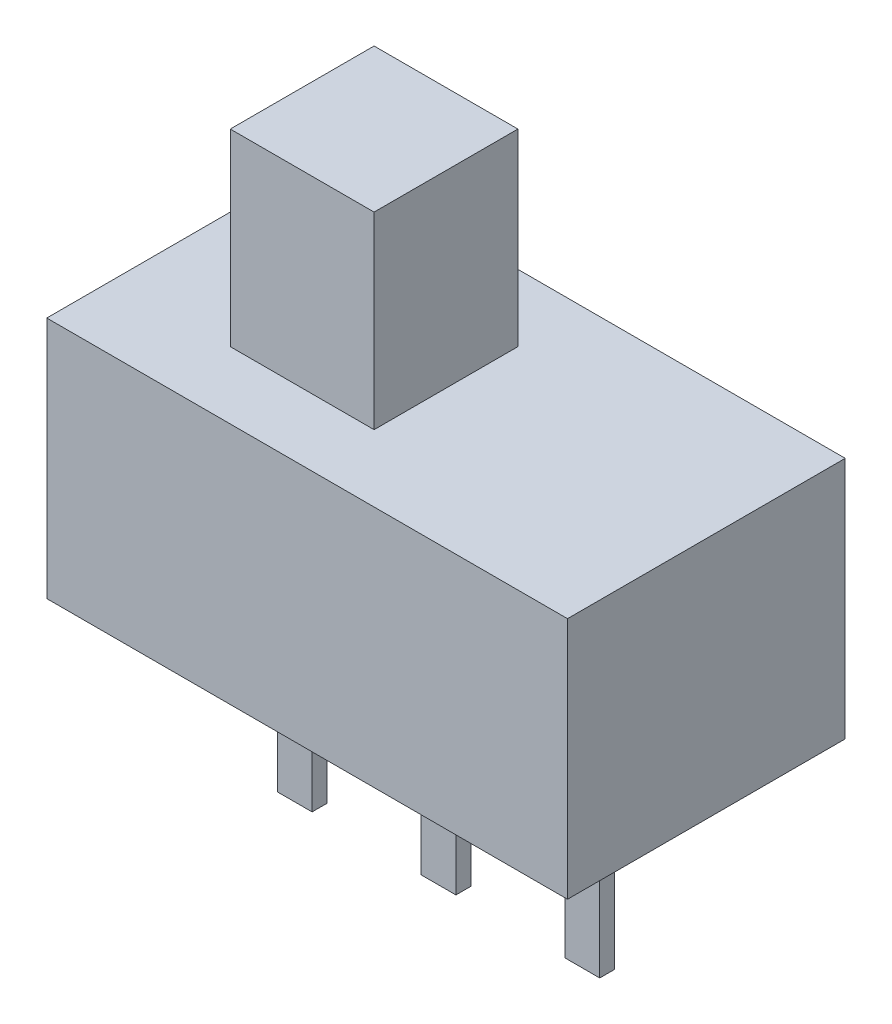
SolidWorks part; units mm, degrees
ref_plane "Plan de face" through (0, 0, 0) normal (0, 0, 1) x (1, 0, 0)
ref_plane "Plan de dessus" through (0, 0, 0) normal (0, 1, 0) x (1, 0, 0)
ref_plane "Plan de droite" through (0, 0, 0) normal (1, 0, 0) x (0, 0, -1)
sketch "Esquisse1" plane through (0, 0, 0) normal (0, 1, 0) x (1, 0, 0)
  line L1 (-5.25, 2.8) -> (5.25, 2.8)
  line L2 (-5.25, 2.8) -> (-5.25, -2.8)
  line L3 (-5.25, -2.8) -> (5.25, -2.8)
  line L4 (5.25, 2.8) -> (5.25, -2.8)
  line L5 (-5.25, 2.8) -> (5.25, -2.8) construction
  line L6 (-5.25, -2.8) -> (5.25, 2.8) construction
  point P0 (0, 0)
  dimension "D1" = 10.5
  dimension "D2" = 5.6
extrude "Boss.-Extru.1" add sketch "Esquisse1" along normal blind 4.9
sketch "Esquisse2" plane through (0, 4.9, 0) normal (0, 1, 0) x (1, 0, 0)
  line L1 (-2.9, 1.45) -> (0, 1.45)
  line L2 (-2.9, 1.45) -> (-2.9, -1.45)
  line L3 (-2.9, -1.45) -> (0, -1.45)
  line L4 (0, 1.45) -> (0, -1.45)
  line L5 (-2.9, 1.45) -> (0, -1.45) construction
  line L6 (-2.9, -1.45) -> (0, 1.45) construction
  point P0 (-1.45, 0)
  dimension "D1" = 2.9
  dimension "D2" = 2.9
extrude "Boss.-Extru.2" add sketch "Esquisse2" along normal blind 3.8
sketch "Esquisse3" plane through (0, 0, 0) normal (0, -1, 0) x (1, 0, 0)
  line L1 (-0.35, 0.15) -> (0.35, 0.15)
  line L2 (-0.35, 0.15) -> (-0.35, -0.15)
  line L3 (-0.35, -0.15) -> (0.35, -0.15)
  line L4 (0.35, 0.15) -> (0.35, -0.15)
  line L5 (-0.35, 0.15) -> (0.35, -0.15) construction
  line L6 (-0.35, -0.15) -> (0.35, 0.15) construction
  line L7 (2.55, 0.15) -> (3.25, 0.15)
  line L8 (2.55, 0.15) -> (2.55, -0.15)
  line L9 (2.55, -0.15) -> (3.25, -0.15)
  line L10 (3.25, 0.15) -> (3.25, -0.15)
  line L11 (2.55, 0.15) -> (3.25, -0.15) construction
  line L12 (2.55, -0.15) -> (3.25, 0.15) construction
  line L13 (-3.25, 0.15) -> (-2.55, 0.15)
  line L14 (-3.25, 0.15) -> (-3.25, -0.15)
  line L15 (-3.25, -0.15) -> (-2.55, -0.15)
  line L16 (-2.55, 0.15) -> (-2.55, -0.15)
  line L17 (-3.25, 0.15) -> (-2.55, -0.15) construction
  line L18 (-3.25, -0.15) -> (-2.55, 0.15) construction
  point P0 (0, 0)
  point P6 (2.9, 0)
  point P11 (-2.9, 0)
  dimension "D1" = 0.7
  dimension "D2" = 0.3
  dimension "D3" = 2.9
  dimension "D4" = 2.9
extrude "Boss.-Extru.3" add sketch "Esquisse3" along normal blind 3.7
